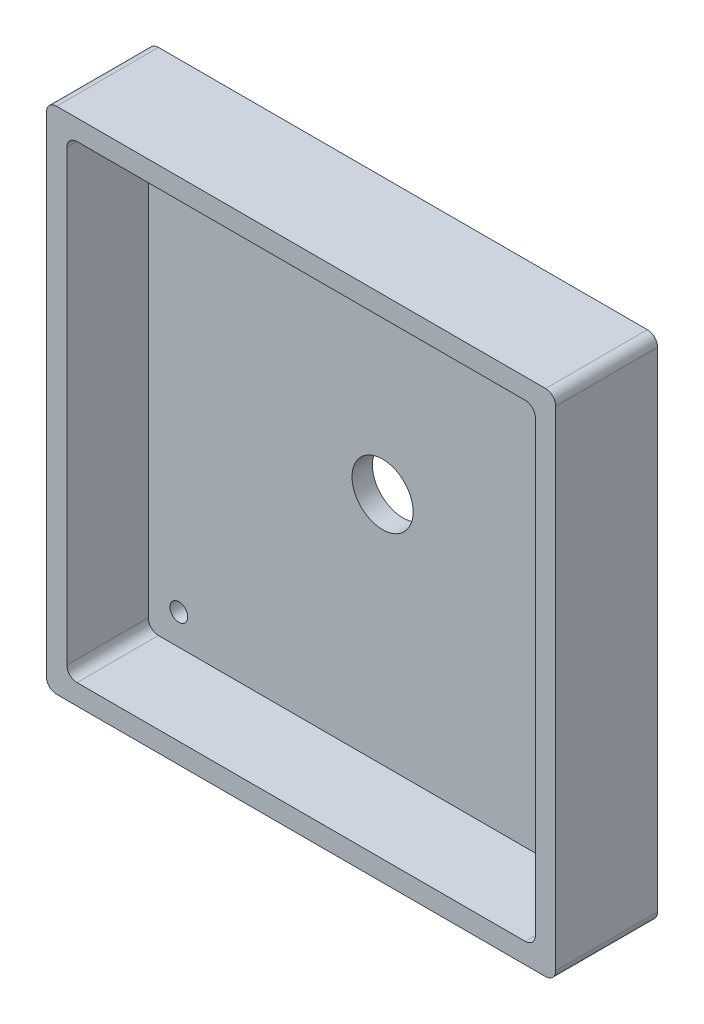
SolidWorks part; units mm, degrees
ref_plane "Front Plane" through (0, 0, 0) normal (0, 0, 1) x (1, 0, 0)
ref_plane "Top Plane" through (0, 0, 0) normal (0, 1, 0) x (1, 0, 0)
ref_plane "Right Plane" through (0, 0, 0) normal (1, 0, 0) x (0, 0, -1)
sketch "Sketch1" plane through (0, 0, 0) normal (0, 0, 1) x (1, 0, 0)
  line L1 (50, 50) -> (-50, 50)
  line L2 (50, 50) -> (50, -50)
  line L3 (50, -50) -> (-50, -50)
  line L4 (-50, 50) -> (-50, -50)
  line L5 (50, 50) -> (-50, -50) construction
  line L6 (50, -50) -> (-50, 50) construction
  point P0 (0, 0)
  dimension "D1" = 100
  dimension "D2" = 100
extrude "Boss-Extrude1" add sketch "Sketch1" along normal blind 20
ref_plane "Plane1" through (0, 0, 20) normal (0, 0, 1) x (1, 0, 0)
sketch "Sketch2" plane through (0, 0, 20) normal (0, 0, 1) x (1, 0, 0)
  line L1 (46, -46) -> (-46, -46)
  line L2 (46, -46) -> (46, 46)
  line L3 (46, 46) -> (-46, 46)
  line L4 (-46, -46) -> (-46, 46)
  line L5 (46, -46) -> (-46, 46) construction
  line L6 (46, 46) -> (-46, -46) construction
  point P0 (0, 0)
  dimension "D1" = 92
  dimension "D2" = 92
extrude "Cut-Extrude1" cut sketch "Sketch2" against normal blind 16
fillet "Fillet1" radius 2 8 edges at (-46, 46, 12) (46, 46, 12) (46, -46, 12) (-46, -46, 12) (50, -50, 10) (-50, -50, 10) (-50, 50, 10) (50, 50, 10)
sketch "Sketch3" plane through (0, 0, 0) normal (0, 0, 1) x (1, 0, 0)
  circle A0 centre (0, 0) radius 6
  circle A1 centre (-40, 40) radius 1.75
  circle A2 centre (40, 40) radius 1.75
  circle A3 centre (40, -40) radius 1.75
  circle A4 centre (-40, -40) radius 1.75
  point P14 (0, 0)
  dimension "D1" = 12
  dimension "D5" = 3.5
  dimension "D2" = 40
  dimension "D3" = 40
  dimension "D4" = 4
extrude "Cut-Extrude2" cut sketch "Sketch3" along normal blind 16
